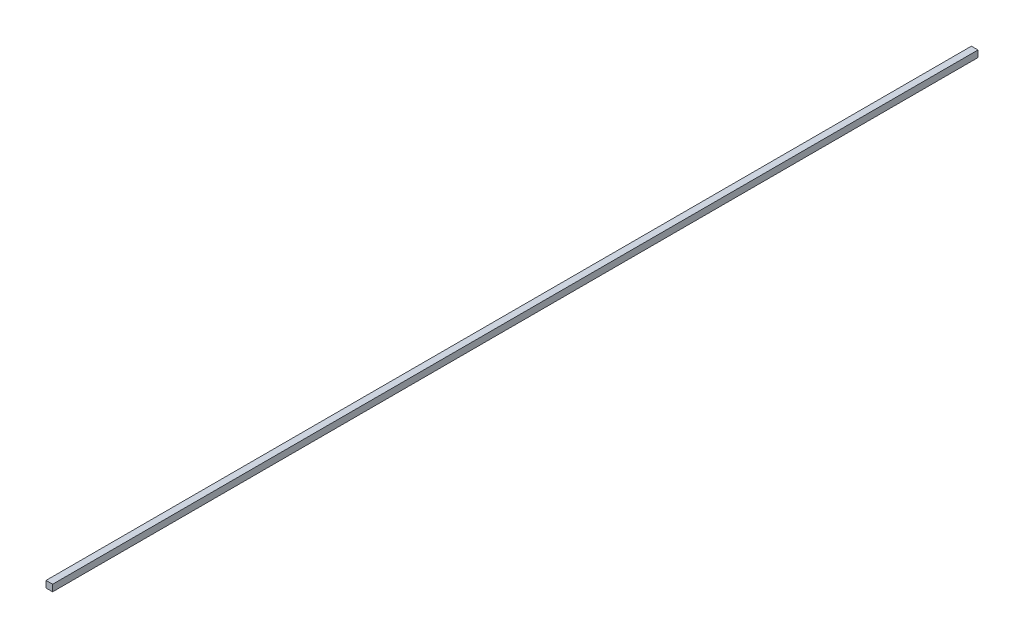
SolidWorks part; units mm, degrees
ref_plane "Plan de face" through (0, 0, 0) normal (0, 0, 1) x (1, 0, 0)
ref_plane "Plan de dessus" through (0, 0, 0) normal (0, 1, 0) x (1, 0, 0)
ref_plane "Plan de droite" through (0, 0, 0) normal (1, 0, 0) x (0, 0, -1)
sketch "Esquisse2" plane through (0, 0, 0) normal (0, 0, 1) x (1, 0, 0)
  line L1 (5, 5) -> (-5, 5)
  line L2 (5, 5) -> (5, -5)
  line L3 (5, -5) -> (-5, -5)
  line L4 (-5, 5) -> (-5, -5)
  line L5 (5, 5) -> (-5, -5) construction
  line L6 (5, -5) -> (-5, 5) construction
  point P0 (0, 0)
  dimension "D1" = 10
extrude "Boss.-Extru.1" add sketch "Esquisse2" along normal mid plane 1400
